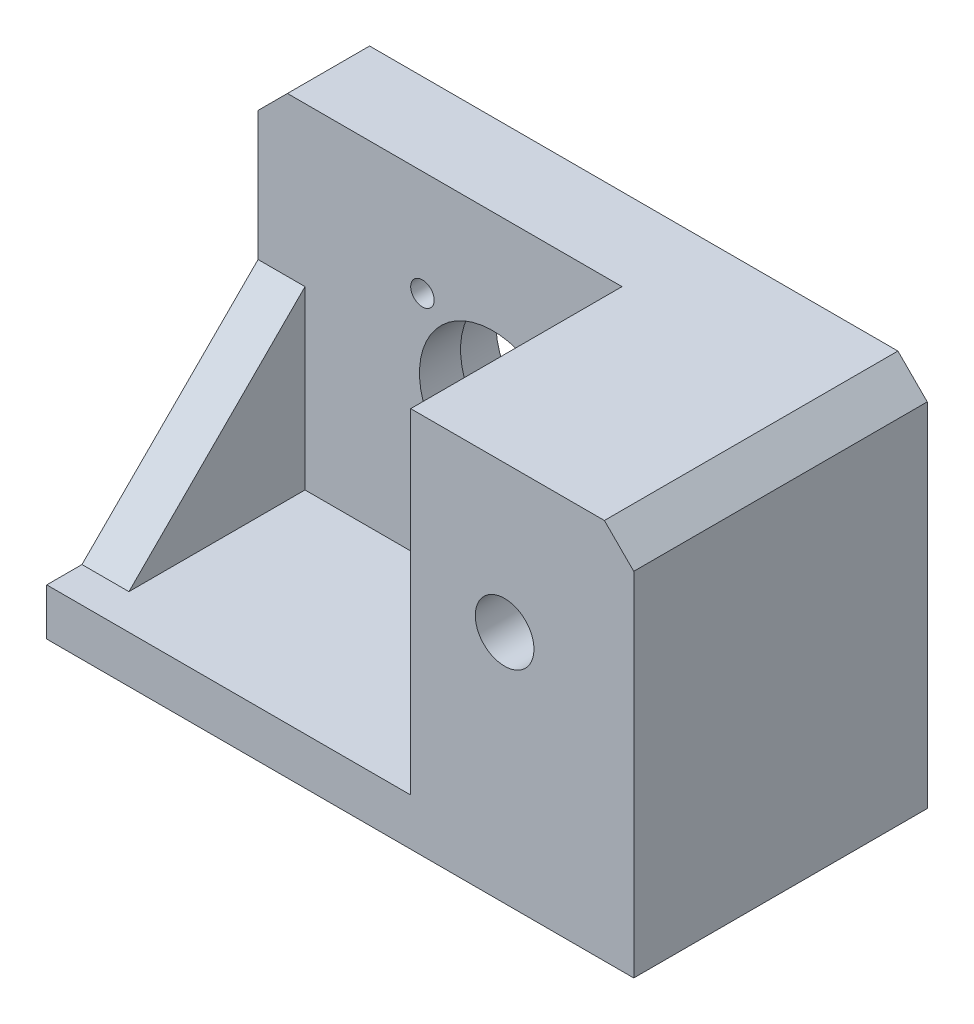
SolidWorks part; units mm, degrees
ref_plane "Front Plane" through (0, 0, 0) normal (0, 0, 1) x (1, 0, 0)
ref_plane "Top Plane" through (0, 0, 0) normal (0, 1, 0) x (1, 0, 0)
ref_plane "Right Plane" through (0, 0, 0) normal (1, 0, 0) x (0, 0, -1)
sketch "Sketch1" plane through (0, 0, 0) normal (0, 0, 1) x (1, 0, 0)
  line L0 (-40, 0) -> (-40, -35)
  line L1 (-40, -35) -> (60, -35)
  line L2 (60, -35) -> (60, 3.08)
  line L3 (60, 3.08) -> (60, 30)
  line L4 (60, 30) -> (-40, 30)
  line L5 (-40, 30) -> (-40, 0)
  circle A0 centre (0, 0) radius 13.5
  dimension "D1" = 27
  dimension "D2" = 100
  dimension "D3" = 35
  dimension "D4" = 65
  dimension "D5" = 60
extrude "Boss-Extrude1" add sketch "Sketch1" along normal blind 14
sketch "Sketch2" plane through (0, 0, 14) normal (0, 0, 1) x (1, 0, 0)
  circle A0 centre (0, 0) radius 13.5
  circle A1 centre (0, 0) radius 12.5
extrude "Boss-Extrude2" add sketch "Sketch2" against normal blind 7
sketch "Sketch11" plane through (0, 0, 14) normal (0, 0, 1) x (1, 0, 0)
  line L5 (-12, -12) -> (12, -12) construction
  line L6 (-12, -12) -> (-12, 12) construction
  line L7 (-12, 12) -> (12, 12) construction
  line L8 (12, -12) -> (12, 12) construction
  line L9 (-12, -12) -> (12, 12) construction
  line L10 (-12, 12) -> (12, -12) construction
  point P0 (0, 0)
hole_wizard "Ø4.0mm Dowel Hole1" positions "Sketch14" profile "Sketch13" hole size "Ø4.0" standard "ISO" end condition through all
sketch "Sketch14" plane through (0, 0, 14) normal (0, 0, 1) x (1, 0, 0)
  point P17 (-12, 12)
  point P20 (12, 12)
  point P23 (12, -12)
  point P26 (-12, -12)
sketch "Sketch13" plane through (-12, 12, 14) normal (1, 0, 0) x (0, -1, 0)
  line L0 (0, 0) -> (0, 14)
  line L1 (0, 14) -> (2, 14)
  line L2 (2, 14) -> (2, 0)
  line L5 (2, 0) -> (0, 0)
  line L11 (0, -6.35) -> (0, 107.95) construction
  dimension "Thru Hole Dia." = 4
  dimension "Thru Hole Depth" = 14
sketch "Sketch16" plane through (0, -35, 0) normal (0, -1, 0) x (1, 0, 0)
  line L0 (60, 14) -> (60, 0) construction
  line L1 (-40, 0) -> (60, 0)
  line L2 (-40, 0) -> (-40, 50)
  line L3 (-40, 50) -> (60, 50)
  line L4 (60, 0) -> (60, 50)
  dimension "D1" = 50
extrude "Boss-Extrude3" add sketch "Sketch16" against normal blind 8
sketch "Sketch17" plane through (60, 0, 0) normal (1, 0, 0) x (0, 0, -1)
  line L0 (-44, -27) -> (-14, 3)
  line L1 (-14, -27) -> (-14, 30) construction
  line L2 (-44, -27) -> (-14, -27)
  line L3 (-14, -27) -> (-14, 3)
  line L4 (-14, -27) -> (-50, -27) construction
  dimension "D1" = 30
  dimension "D2" = 30
extrude "Boss-Extrude4" add sketch "Sketch17" against normal blind 8
ref_plane "Plane1" through (10, 0, 0) normal (1, 0, 0) x (0, 0, -1)
mirror "Mirror1" about plane through (10, 0, 0) normal (1, 0, 0) of "Boss-Extrude4"
chamfer "Chamfer2" distance 5 angle 45 1 edges at (-40, 30, 7)
sketch "Sketch18" plane through (0, 0, 50) normal (0, 0, 1) x (1, 0, 0)
  line L0 (-35, 30) -> (60, 30) construction
  line L1 (60, -35) -> (22, -35)
  line L2 (60, -35) -> (60, 30)
  line L3 (60, 30) -> (22, 30)
  line L4 (22, -35) -> (22, 30)
  dimension "D2" = 38
extrude "Boss-Extrude5" add sketch "Sketch18" against normal blind 44
sketch "Sketch15" plane through (0, 0, 0) normal (0, 0, -1) x (-1, 0, 0)
  line L0 (-60, 5) -> (-38, 5) construction
  circle A0 centre (-38, 5) radius 5
  dimension "D2" = 5
  dimension "D1" = 22
extrude "Cut-Extrude1" cut sketch "Sketch15" against normal through all
chamfer "Chamfer3" distance 5 angle 45 1 edges at (60, 30, 25)
